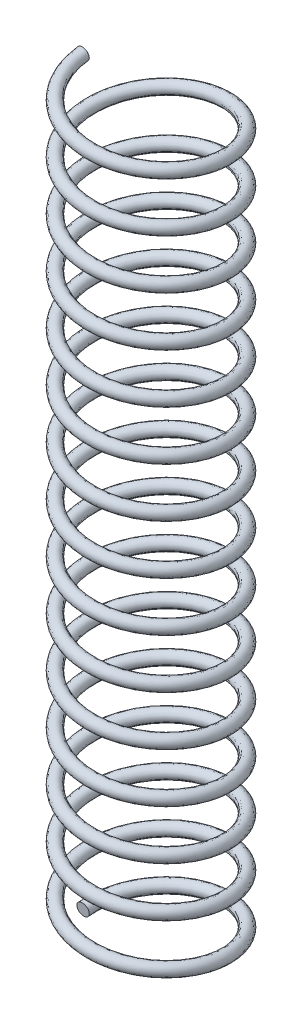
SolidWorks part; units mm, degrees
material "AISI 1020"
ref_plane "Front Plane" through (0, 0, 0) normal (0, 0, 1) x (1, 0, 0)
ref_plane "Top Plane" through (0, 0, 0) normal (0, 1, 0) x (1, 0, 0)
ref_plane "Right Plane" through (0, 0, 0) normal (1, 0, 0) x (0, 0, -1)
sketch "Sketch1" plane through (0, 0, 0) normal (0, 1, 0) x (1, 0, 0)
  circle A0 centre (0, 0) radius 2.75
  dimension "D1" = 5.5
curve "Helix/Spiral1" pitch 2 height 30 turns 15
sweep "Sweep1" add path "Helix/Spiral1" circular profile diameter 0.5 parameters "D3"=0.5
